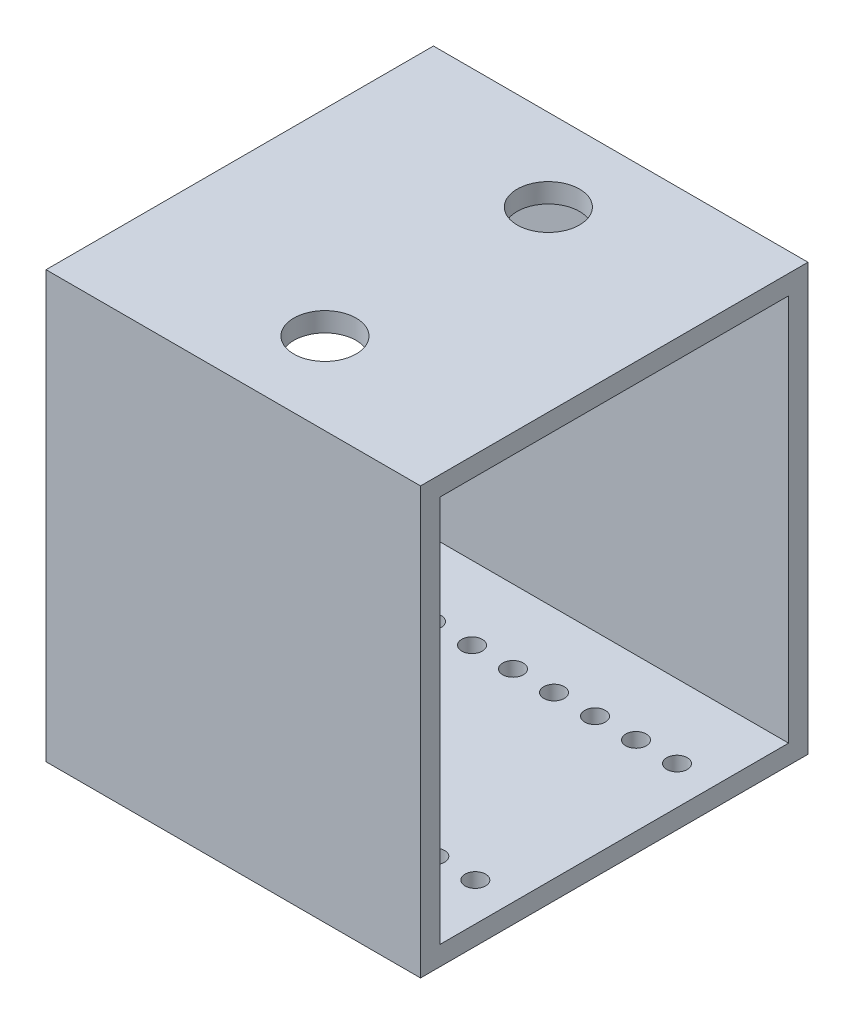
SolidWorks part; units mm, degrees
ref_plane "Front Plane" through (0, 0, 0) normal (0, 0, 1) x (1, 0, 0)
ref_plane "Top Plane" through (0, 0, 0) normal (0, 1, 0) x (1, 0, 0)
ref_plane "Right Plane" through (0, 0, 0) normal (1, 0, 0) x (0, 0, -1)
sketch "Sketch1" plane through (0, 0, 0) normal (0, 0, 1) x (1, 0, 0)
  line L0 (8, 30) -> (-47, 30)
  line L1 (-47, 30) -> (-47, -30)
  line L2 (-47, -30) -> (8, -30)
  line L3 (0, 0) -> (-47, 0) construction
  line L4 (8, 33) -> (-50, 33)
  line L5 (-50, 33) -> (-50, -33)
  line L6 (-50, -33) -> (8, -33)
  line L7 (8, 30) -> (8, 33)
  line L8 (8, -30) -> (8, -33)
  dimension "D2" = 60
  dimension "D3" = 55
  dimension "D4" = 50
  dimension "D1" = 3
extrude "Boss-Extrude1" add sketch "Sketch1" along normal blind 60
sketch "Sketch2" plane through (0, -33, 0) normal (0, -1, 0) x (1, 0, 0)
  line L0 (-50, 60) -> (8, 60) construction
  line L1 (-36, 45.62) -> (-36, 60) construction
  line L2 (-36, 14.38) -> (-36, 0) construction
  line L3 (-50, 0) -> (8, 0) construction
  circle A0 centre (-36, 45.62) radius 1.59
  circle A1 centre (-29.65, 45.62) radius 1.59
  circle A2 centre (-23.3, 45.62) radius 1.59
  circle A3 centre (-16.95, 45.62) radius 1.59
  circle A4 centre (-10.6, 45.62) radius 1.59
  circle A5 centre (-4.25, 45.62) radius 1.59
  circle A6 centre (2.1, 45.62) radius 1.59
  circle A7 centre (-29.65, 14.38) radius 1.59
  circle A8 centre (-23.3, 14.38) radius 1.59
  circle A9 centre (-16.95, 14.38) radius 1.59
  circle A10 centre (-10.6, 14.38) radius 1.59
  circle A11 centre (-4.25, 14.38) radius 1.59
  circle A12 centre (2.1, 14.38) radius 1.59
  circle A13 centre (-36, 14.38) radius 1.59
  dimension "D1" = 3.18
  dimension "D5" = 7
  dimension "D6" = 6.35
  dimension "D2" = 11
  dimension "D4" = 14.38
  dimension "D7" = 31.24
  dimension "D3" = 2
extrude "Cut-Extrude1" cut sketch "Sketch2" against normal up to next
sketch "Sketch3" plane through (-50, 0, 0) normal (-1, 0, 0) x (0, 0, 1)
  line L0 (30, 33) -> (30, -33) construction
  line L1 (60, 33) -> (0, 33) construction
  line L2 (60, -33) -> (0, -33) construction
  line L3 (0, 33) -> (0, -33) construction
  line L4 (9, 24) -> (51, 24)
  line L5 (9, 24) -> (9, -24)
  line L6 (9, -24) -> (51, -24)
  line L7 (51, 24) -> (51, -24)
  line L8 (9, 24) -> (51, -24) construction
  line L9 (9, -24) -> (51, 24) construction
  point P6 (30, 0)
  dimension "D1" = 9
  dimension "D2" = 9
extrude "Cut-Extrude2" cut sketch "Sketch3" against normal blind 60
sketch "Sketch6" plane through (-47, 0, 0) normal (1, 0, 0) x (0, 0, -1)
  line L0 (-60, 30) -> (-60, -30)
  line L1 (-57, 30) -> (-57, -30)
  line L2 (-60, 30) -> (-57, 30)
  line L3 (-60, -30) -> (-57, -30)
  line L4 (-30, 24) -> (-30, 13.5335) construction
  line L5 (-51, 24) -> (-9, 24) construction
  line L6 (0, 30) -> (-3, 30)
  line L7 (0, 30) -> (0, -30)
  line L8 (0, -30) -> (-3, -30)
  line L9 (-3, 30) -> (-3, -30)
  dimension "D1" = 3
extrude "Boss-Extrude2" add sketch "Sketch6" along normal up to surface (55 mm away) up to face at (8, -31.5, 30)
extrude "Cut-Extrude3" cut sketch "Sketch4" against normal blind 109.474
sketch "Sketch4" plane through (-21.6092, 30, -179.0244) normal (0, -1, 0) x (1, 0, 0)
  line L1 (29.6092, 209.0244) -> (-25.4143, 209.0244) construction
  line L4 (2.1092, 179.0244) -> (2.0975, 209.0244) construction
  circle A0 centre (2.1042, 226.3244) radius 4.826
  circle A1 centre (2.1042, 191.7244) radius 4.826
